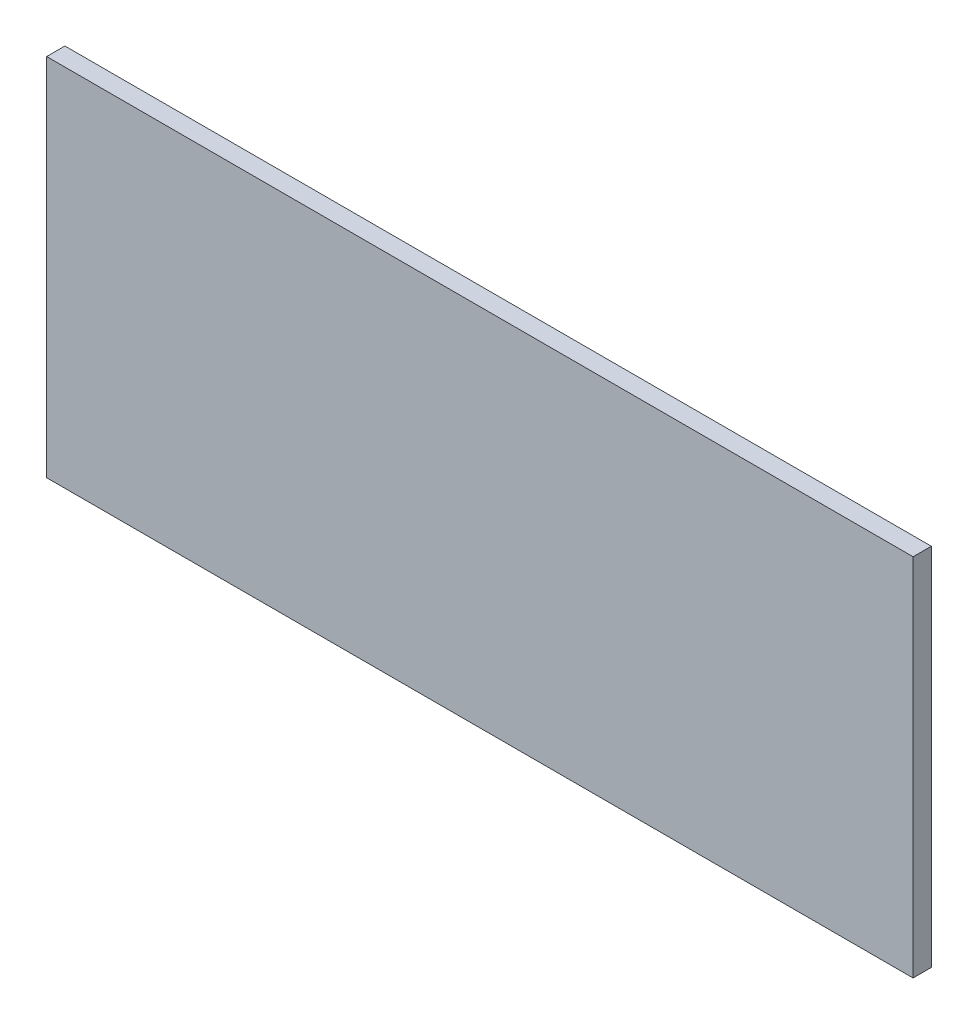
SolidWorks part; units mm, degrees
ref_plane "Front Plane" through (0, 0, 0) normal (0, 0, 1) x (1, 0, 0)
ref_plane "Top Plane" through (0, 0, 0) normal (0, 1, 0) x (1, 0, 0)
ref_plane "Right Plane" through (0, 0, 0) normal (1, 0, 0) x (0, 0, -1)
sketch "Sketch1" plane through (0, 0, 0) normal (0, 0, 1) x (1, 0, 0)
  line L1 (-91.7627, -11.7061) -> (98.2373, -11.7061)
  line L2 (-91.7627, -11.7061) -> (-91.7627, -91.7061)
  line L3 (-91.7627, -91.7061) -> (98.2373, -91.7061)
  line L4 (98.2373, -11.7061) -> (98.2373, -91.7061)
  point P4 (-70.8842, -94.0831)
  point P5 (-91.7627, -94.0507)
  point P6 (98.2373, -91.7061)
  dimension "D1" = 80
  dimension "D2" = 190
extrude "Boss-Extrude1" add sketch "Sketch1" along normal blind 4
